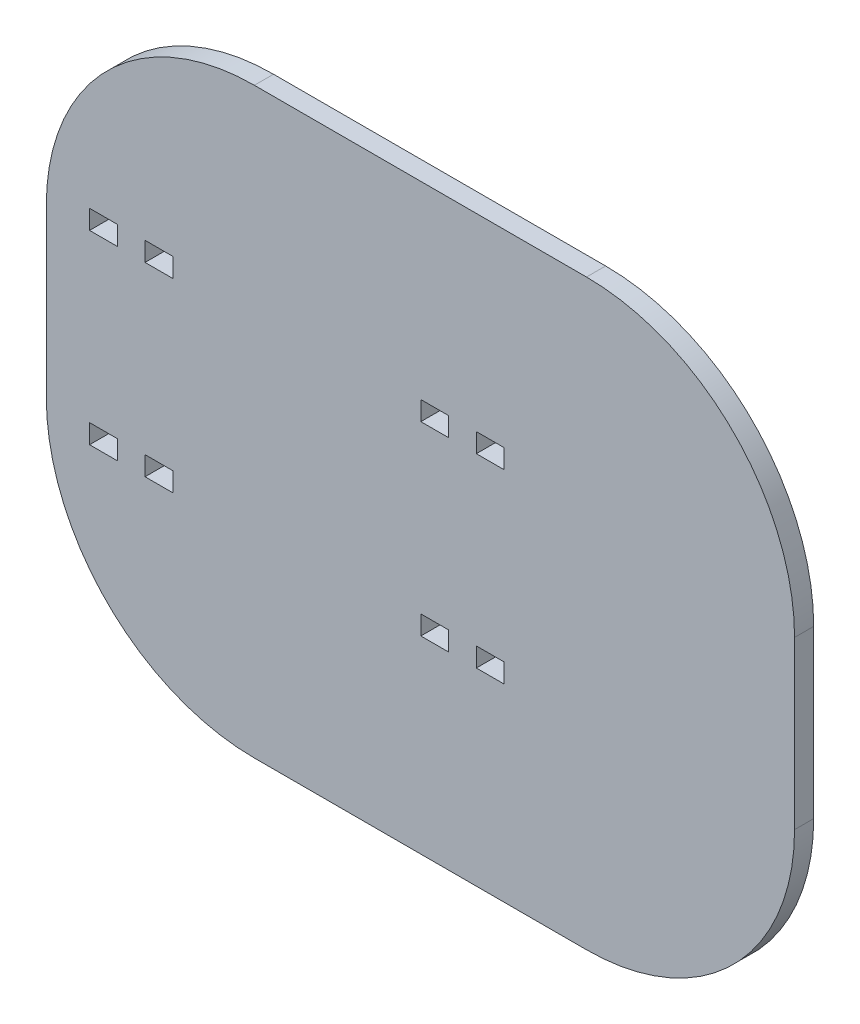
SolidWorks part; units mm, degrees
ref_plane "Front Plane" through (0, 0, 0) normal (0, 0, 1) x (1, 0, 0)
ref_plane "Top Plane" through (0, 0, 0) normal (0, 1, 0) x (1, 0, 0)
ref_plane "Right Plane" through (0, 0, 0) normal (1, 0, 0) x (0, 0, -1)
sketch "Sketch1" plane through (0, 0, 0) normal (0, 0, 1) x (1, 0, 0)
  line L1 (114.173, -88.9) -> (-114.173, -88.9)
  line L2 (114.173, -88.9) -> (114.173, 88.9)
  line L3 (114.173, 88.9) -> (-114.173, 88.9)
  line L4 (-114.173, -88.9) -> (-114.173, 88.9)
  line L5 (114.173, -88.9) -> (-114.173, 88.9) construction
  line L6 (114.173, 88.9) -> (-114.173, -88.9) construction
  point P0 (0, 0)
  dimension "D1" = 228.346
  dimension "D2" = 177.8
extrude "Boss-Extrude1" add sketch "Sketch1" along normal blind 5.842
fillet "Fillet1" radius 63.5 1 edges at (-114.173, 88.9, 2.921)
fillet "Fillet2" radius 63.5 1 edges at (-114.173, -88.9, 2.921)
fillet "Fillet3" radius 63.5 2 edges at (114.173, 88.9, 2.921) (114.173, -88.9, 2.921)
sketch "Sketch2" plane through (0, 0, 5.842) normal (0, 0, 1) x (1, 0, 0)
  line L0 (25.527, -88.9) -> (25.527, 88.9) construction
  line L1 (-50.673, -88.9) -> (50.673, -88.9) construction
  line L2 (50.673, 88.9) -> (-50.673, 88.9) construction
  line L3 (-114.173, 25.4) -> (-114.173, -25.4) construction
  line L4 (25.527, -31.242) -> (0.127, -31.242) construction
  line L5 (25.527, 31.242) -> (0.127, 31.242) construction
  line L6 (8.5937, -25.4) -> (17.0603, -25.4) construction
  line L7 (0.127, -31.242) -> (8.5937, -31.242)
  line L8 (0.127, -31.242) -> (0.127, -25.4)
  line L9 (0.127, -25.4) -> (8.5937, -25.4)
  line L10 (8.5937, -31.242) -> (8.5937, -25.4)
  line L11 (8.5937, 25.4) -> (17.0603, 25.4) construction
  line L12 (17.0603, -25.4) -> (25.527, -25.4)
  line L13 (17.0603, -25.4) -> (17.0603, -31.242)
  line L14 (17.0603, -31.242) -> (25.527, -31.242)
  line L15 (25.527, -25.4) -> (25.527, -31.242)
  line L16 (0.127, 31.242) -> (8.5937, 31.242)
  line L17 (0.127, 31.242) -> (0.127, 25.4)
  line L18 (0.127, 25.4) -> (8.5937, 25.4)
  line L19 (8.5937, 31.242) -> (8.5937, 25.4)
  line L20 (-100.965, -31.242) -> (-75.565, -31.242) construction
  line L21 (17.0603, 25.4) -> (25.527, 25.4)
  line L22 (17.0603, 25.4) -> (17.0603, 31.242)
  line L23 (17.0603, 31.242) -> (25.527, 31.242)
  line L24 (25.527, 25.4) -> (25.527, 31.242)
  line L25 (-92.4983, -25.4) -> (-84.0317, -25.4) construction
  line L26 (-100.965, -31.242) -> (-92.4983, -31.242)
  line L27 (-100.965, 31.242) -> (-75.565, 31.242) construction
  line L28 (-100.965, -31.242) -> (-100.965, -25.4)
  line L29 (-100.965, -25.4) -> (-92.4983, -25.4)
  line L30 (-92.4983, -31.242) -> (-92.4983, -25.4)
  line L31 (-92.4983, 25.4) -> (-84.0317, 25.4) construction
  line L32 (-84.0317, -25.4) -> (-75.565, -25.4)
  line L33 (-84.0317, -25.4) -> (-84.0317, -31.242)
  line L34 (-84.0317, -31.242) -> (-75.565, -31.242)
  line L35 (-75.565, -25.4) -> (-75.565, -31.242)
  line L36 (-100.965, 31.242) -> (-92.4983, 31.242)
  line L37 (-100.965, 31.242) -> (-100.965, 25.4)
  line L38 (-100.965, 25.4) -> (-92.4983, 25.4)
  line L39 (-92.4983, 31.242) -> (-92.4983, 25.4)
  line L40 (-75.565, 31.242) -> (-84.0317, 31.242)
  line L41 (-75.565, 31.242) -> (-75.565, 25.4)
  line L42 (-75.565, 25.4) -> (-84.0317, 25.4)
  line L43 (-84.0317, 31.242) -> (-84.0317, 25.4)
  dimension "D1" = 139.7
  dimension "D2" = 57.658
  dimension "D3" = 57.658
  dimension "D4" = 25.4
  dimension "D5" = 25.4
  dimension "D6" = 5.842
  dimension "D7" = 5.842
  dimension "D8" = 25.4
  dimension "D9" = 13.208
  dimension "D10" = 13.208
extrude "Cut-Extrude1" cut sketch "Sketch2" against normal through all
